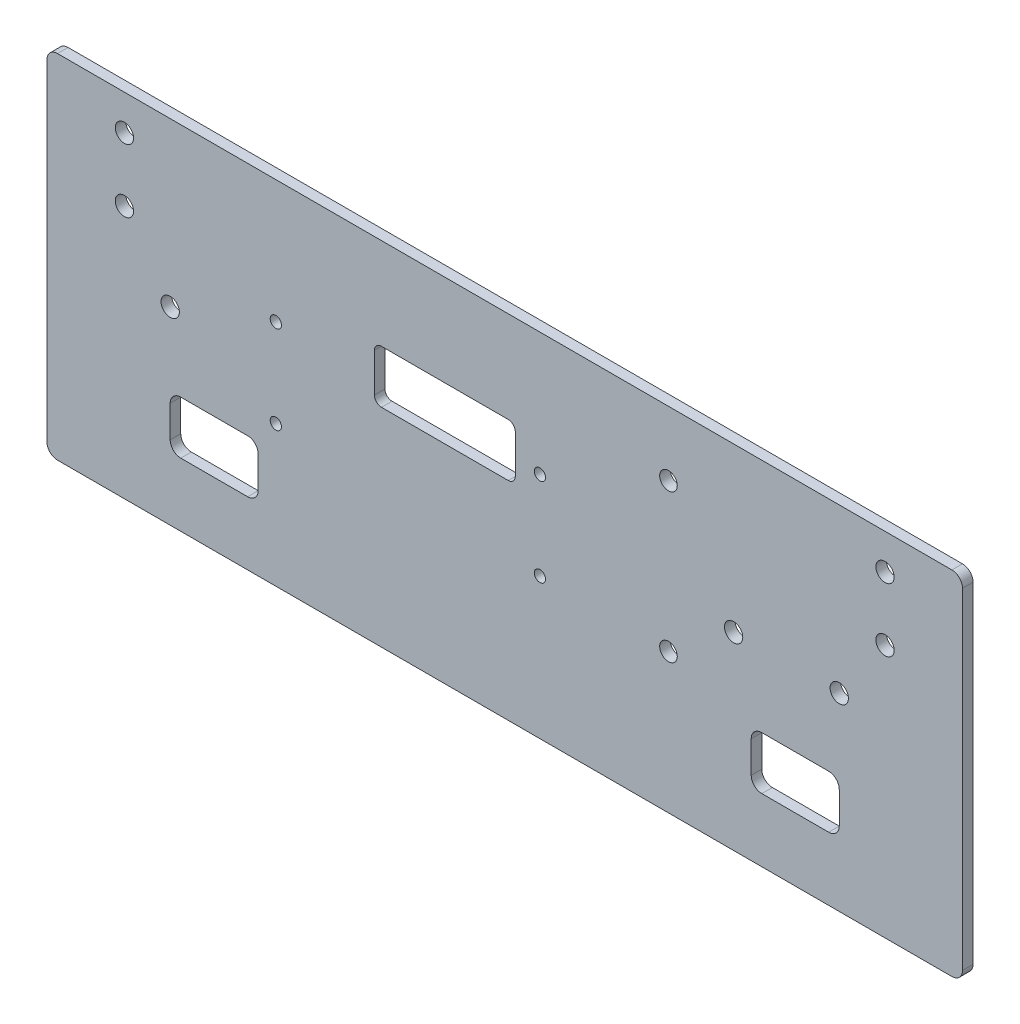
SolidWorks part; units mm, degrees
material "Thornel Mat VMA"
ref_plane "前视基准面" through (0, 0, 0) normal (0, 0, 1) x (1, 0, 0)
ref_plane "上视基准面" through (0, 0, 0) normal (0, 1, 0) x (1, 0, 0)
ref_plane "右视基准面" through (0, 0, 0) normal (1, 0, 0) x (0, 0, -1)
other "Configuration Table"
sketch "草图1" plane through (0, 0, 0) normal (0, 0, 1) x (1, 0, 0)
  line L1 (130, -50) -> (-130, -50)
  line L2 (130, -50) -> (130, 50)
  line L3 (130, 50) -> (-130, 50)
  line L4 (-130, -50) -> (-130, 50)
  line L5 (130, -50) -> (-130, 50) construction
  line L6 (130, 50) -> (-130, -50) construction
  point P0 (0, 0)
  dimension "D1" = 100
  dimension "D2" = 260
extrude "凸台-拉伸1" add sketch "草图1" along normal blind 3
fillet "圆角1" radius 3 4 edges at (130, 50, 1.5) (130, -50, 1.5) (-130, -50, 1.5) (-130, 50, 1.5)
sketch "草图4" plane through (0, 0, 3) normal (0, 0, 1) x (1, 0, 0)
  line L0 (-130, -17) -> (130, -17) construction
  line L1 (-130, 47) -> (-130, -47) construction
  line L2 (130, -47) -> (130, 47) construction
  line L3 (127, 50) -> (-127, 50) construction
  line L4 (0, 50) -> (0, -50) construction
  line L5 (-95, -17) -> (-70, -17)
  line L6 (-95, -17) -> (-95, -32)
  line L7 (-95, -32) -> (-70, -32)
  line L8 (-70, -17) -> (-70, -32)
  line L9 (-127, -50) -> (127, -50) construction
  line L10 (70, -17) -> (70, -32)
  line L11 (95, -32) -> (70, -32)
  line L12 (95, -17) -> (95, -32)
  line L13 (95, -17) -> (70, -17)
  dimension "D1" = 67
  dimension "D2" = 25
  dimension "D3" = 70
  dimension "D4" = 15
extrude "切除-拉伸3" cut sketch "草图4" against normal blind 500
fillet "圆角2" radius 3 8 edges at (95, -32, 1.5) (70, -32, 1.5) (95, -17, 1.5) (70, -17, 1.5) (-70, -17, 1.5) (-70, -32, 1.5) (-95, -32, 1.5) (-95, -17, 1.5)
sketch "草图6" plane through (0, 0, 3) normal (0, 0, 1) x (1, 0, 0)
  line L0 (127, 50) -> (-127, 50) construction
  line L1 (-65, 15) -> (10, 15) construction
  line L2 (-65, 15) -> (-65, -10) construction
  line L3 (-65, -10) -> (10, -10) construction
  line L4 (10, 15) -> (10, -10) construction
  line L5 (-130, 47) -> (-130, -47) construction
  line L7 (-37, 24) -> (3, 24)
  line L8 (-37, 24) -> (-37, 9)
  line L9 (-37, 9) -> (3, 9)
  line L10 (3, 24) -> (3, 9)
  circle A0 centre (-65, 15) radius 1.6
  circle A1 centre (10, 15) radius 1.6
  circle A2 centre (10, -10) radius 1.6
  circle A3 centre (-65, -10) radius 1.6
  dimension "D5" = 3.2
  dimension "D1" = 75
  dimension "D2" = 25
  dimension "D3" = 35
  dimension "D4" = 65
  dimension "D6" = 40
  dimension "D7" = 15
  dimension "D8" = 28
  dimension "D9" = 6
extrude "切除-拉伸5" cut sketch "草图6" against normal blind 10
fillet "圆角4" radius 2 4 edges at (3, 24, 1.5) (3, 9, 1.5) (-37, 9, 1.5) (-37, 24, 1.5)
sketch "草图7" plane through (0, 0, 3) normal (0, 0, 1) x (1, 0, 0)
  line L0 (46.5, 50) -> (46.5, -50) construction
  line L1 (127, 50) -> (-127, 50) construction
  line L2 (-127, -50) -> (127, -50) construction
  line L3 (130, -47) -> (130, 47) construction
  circle A0 centre (46.5, 31.7) radius 2.5
  circle A1 centre (46.5, -10.3) radius 2.5
  dimension "D2" = 42
  dimension "D3" = 5
  dimension "D4" = 18.3
  dimension "D1" = 83.5
extrude "切除-拉伸6" cut sketch "草图7" against normal blind 10
sketch "草图8" plane through (0, 0, 3) normal (0, 0, 1) x (1, 0, 0)
  line L0 (0, 50) -> (0, -50) construction
  line L1 (127, 50) -> (-127, 50) construction
  line L2 (-127, -50) -> (127, -50) construction
  line L3 (-130, 47) -> (-130, -47) construction
  line L4 (-108, 40) -> (-108, 22) construction
  circle A0 centre (-108, 40) radius 2.6
  circle A1 centre (108, 40) radius 2.6
  circle A2 centre (-108, 22) radius 2.6
  circle A3 centre (108, 22) radius 2.6
  circle A4 centre (-95, 3.7) radius 2.6
  circle A5 centre (95, 3.7) radius 2.6
  dimension "D1" = 5.2
  dimension "D2" = 22
  dimension "D3" = 10
  dimension "D5" = 5.2
  dimension "D6" = 35
  dimension "D7" = 46.3
  dimension "D4" = 18
extrude "切除-拉伸7" cut sketch "草图8" against normal blind 10
sketch "草图9" plane through (0, 0, 3) normal (0, 0, 1) x (1, 0, 0)
  line L0 (130, -47) -> (130, 47) construction
  line L1 (127, 50) -> (-127, 50) construction
  circle A0 centre (65, 3.7) radius 2.6
  dimension "D1" = 5.2
  dimension "D2" = 65
  dimension "D3" = 46.3
extrude "切除-拉伸8" cut sketch "草图9" against normal blind 10
